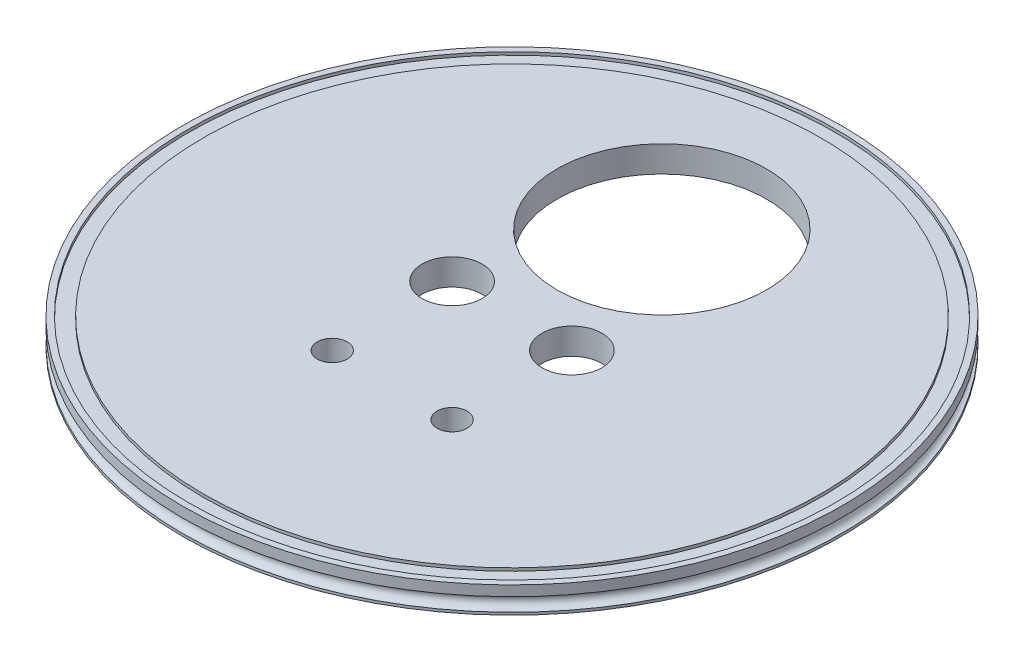
SolidWorks part; units mm, degrees
material "AISI 304"
ref_plane "Front Plane" through (0, 0, 0) normal (0, 0, 1) x (1, 0, 0)
ref_plane "Top Plane" through (0, 0, 0) normal (0, 1, 0) x (1, 0, 0)
ref_plane "Right Plane" through (0, 0, 0) normal (1, 0, 0) x (0, 0, -1)
sketch "Sketch1" plane through (0, 0, 0) normal (0, 0, 1) x (1, 0, 0)
  line L0 (0, 12.2638) -> (0, -11.9635) construction
  line L1 (0, 1.365) -> (0, -9.7475)
  line L2 (0, -9.7475) -> (120.65, -9.7475)
  line L3 (139.7, -9.7475) -> (139.7, -8.668)
  line L4 (139.7, 1.365) -> (137.16, 1.365)
  line L5 (139.7, -2.953) -> (139.7, 1.365)
  line L6 (130.81, 1.365) -> (130.81, 0.095)
  line L7 (130.81, 0.095) -> (137.16, 0.095)
  line L8 (137.16, 0.095) -> (137.16, 1.365)
  line L9 (120.65, -9.7475) -> (120.65, -7.2075)
  line L10 (120.65, -7.2075) -> (127, -7.2075)
  line L11 (127, -7.2075) -> (127, -9.7475)
  line L12 (130.81, 1.365) -> (0, 1.365)
  line L13 (127, -9.7475) -> (139.7, -9.7475)
  arc A0 (139.7, -2.953) -> (139.7, -8.668) centre (139.7, -5.8105) ccw
  dimension "D2" = 5.715
  dimension "D1" = 11.1125
  dimension "D3" = 4.318
  dimension "D4" = 1.0795
  dimension "D5" = 2.54
  dimension "D6" = 1.27
  dimension "D7" = 6.35
  dimension "D8" = 6.35
  dimension "D9" = 127
  dimension "D10" = 139.7
  dimension "D11" = 2.54
revolve "Revolve1" add sketch "Sketch1" angle 360 about L0
sketch "Sketch2" plane through (0, 1.365, 0) normal (0, 1, 0) x (1, 0, 0)
  circle A0 centre (25.4, -50.8) radius 6.35
  circle A1 centre (-25.4, -50.8) radius 6.35
  dimension "D1" = 12.7
  dimension "D2" = 12.7
  dimension "D3" = 50.8
  dimension "D4" = 50.8
  dimension "D5" = 25.4
  dimension "D6" = 25.4
extrude "Cut-Extrude1" cut sketch "Sketch2" against normal through all
sketch "Sketch3" plane through (0, -9.7475, 0) normal (0, -1, 0) x (-1, 0, 0)
  circle A0 centre (-25.4, 0) radius 12.7
  circle A1 centre (25.4, 0) radius 12.7
  circle A2 centre (-25.4, -50.8) radius 6.35 construction
  circle A3 centre (25.4, -50.8) radius 6.35 construction
  dimension "D1" = 25.4
  dimension "D2" = 25.4
  dimension "D3" = 25.4
  dimension "D4" = 25.4
  dimension "D5" = 50.8
  dimension "D6" = 50.8
extrude "Cut-Extrude2" cut sketch "Sketch3" against normal through all
sketch "Sketch4" plane through (0, 1.365, 0) normal (0, 1, 0) x (1, 0, 0)
  circle A0 centre (0, 63.5) radius 44.45
  circle A1 centre (25.4, 0) radius 12.7 construction
  circle A2 centre (-25.4, 0) radius 12.7 construction
  dimension "D1" = 88.9
  dimension "D2" = 63.5
  dimension "D3" = 25.4
extrude "Cut-Extrude3" cut sketch "Sketch4" against normal through all
